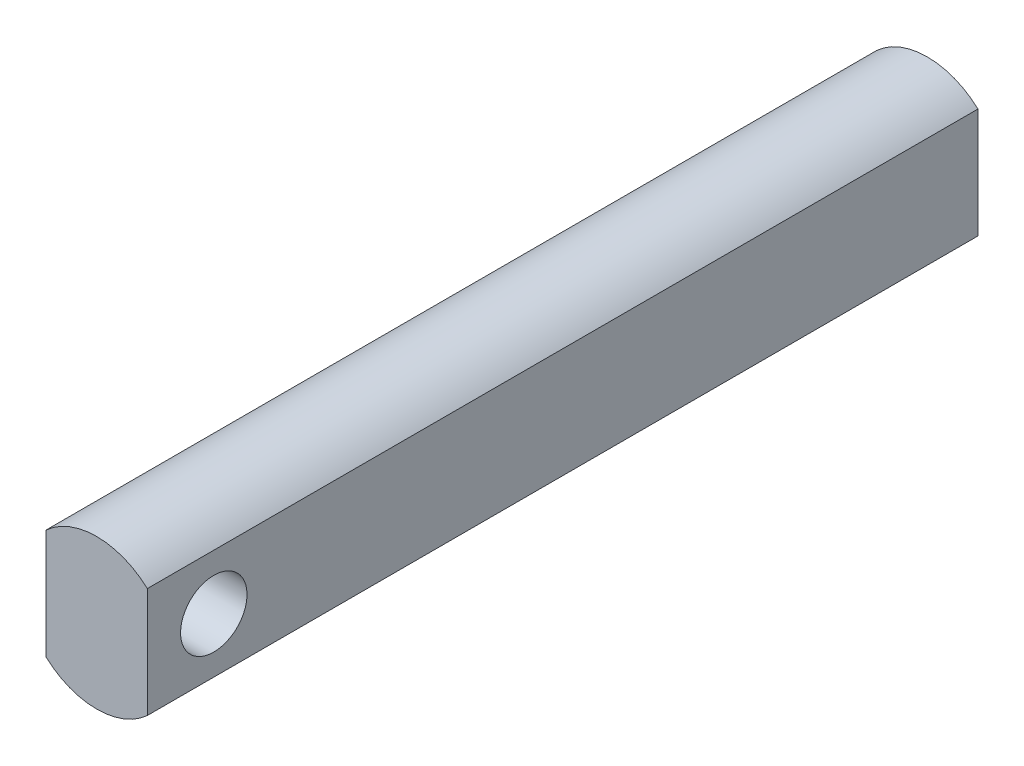
SolidWorks part; units mm, degrees
ref_plane "Спереди" through (0, 0, 0) normal (0, 0, 1) x (1, 0, 0)
ref_plane "Сверху" through (0, 0, 0) normal (0, 1, 0) x (1, 0, 0)
ref_plane "Справа" through (0, 0, 0) normal (1, 0, 0) x (0, 0, -1)
sketch "Эскиз1" plane through (0, 0, 0) normal (0, 0, 1) x (1, 0, 0)
  line L2 (-3.05, 2.3087) -> (-3.05, -4.3087)
  line L3 (3.05, -4.3087) -> (3.05, 2.3087)
  arc A2 (-3.05, -4.3087) -> (3.05, -4.3087) centre (0, -1) ccw
  arc A3 (3.05, 2.3087) -> (-3.05, 2.3087) centre (0, -1) ccw
extrude "Бобышка-Вытянуть1" add sketch "Эскиз1" along normal blind 50
sketch "Эскиз2" plane through (-3.05, 0, 0) normal (-1, 0, 0) x (0, 0, 1)
  line L0 (50, 2.3087) -> (50, -4.3087) construction
  circle A0 centre (46, -1) radius 2
  point P5 (50, -1)
  dimension "D1" = 4
  dimension "D2" = 2
extrude "Вырез-Вытянуть1" cut sketch "Эскиз2" against normal through all
sketch "Эскиз3" plane through (3.05, 0, 0) normal (1, 0, 0) x (0, 0, -1)
  circle A0 centre (-46, -1) radius 2 construction
  circle A1 centre (-46, -1) radius 2
sketch "Эскиз4" plane through (-3.05, 0, 0) normal (-1, 0, 0) x (0, 0, 1)
  circle A0 centre (46, -1) radius 2 construction
  circle A1 centre (46, -1) radius 2
